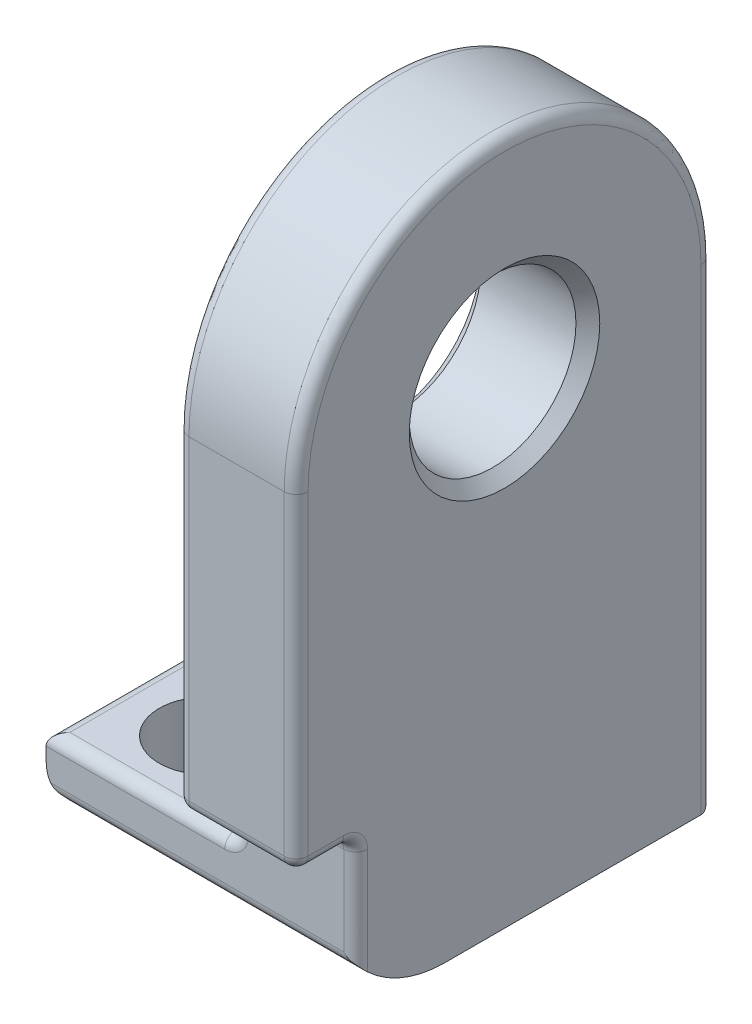
SolidWorks part; units mm, degrees
ref_plane "前视基准面" through (0, 0, 0) normal (0, 0, 1) x (1, 0, 0)
ref_plane "上视基准面" through (0, 0, 0) normal (0, 1, 0) x (1, 0, 0)
ref_plane "右视基准面" through (0, 0, 0) normal (1, 0, 0) x (0, 0, -1)
sketch "草图1" plane through (0, 0, 0) normal (1, 0, 0) x (0, 0, -1)
  line L0 (3.5, 0) -> (3.5, -8)
  line L1 (-3.5, 0) -> (-3.5, -8)
  line L2 (3.5, -8) -> (-3.5, -8)
  circle A0 centre (0, 0) radius 1.4
  arc A1 (3.5, 0) -> (-3.5, 0) centre (0, 0) ccw
  dimension "D1" = 3.5
  dimension "D2" = 8
extrude "凸台-拉伸1" add sketch "草图1" along normal blind 2
sketch "草图2" plane through (0, -8, 0) normal (0, -1, 0) x (1, 0, 0)
  line L0 (2, 3.5) -> (2, -3.5) construction
  line L1 (2, -3.5) -> (-3.2, -3.5)
  line L3 (2, 3.5) -> (-3.2, 3.5)
  line L4 (-3.2, -3.5) -> (-3.2, 3.5)
  line L6 (0, 3.5) -> (0, -3.5) construction
  line L7 (2, -3.5) -> (0, -3.5) construction
  line L8 (2, -3.5) -> (2, 3.5)
  line L9 (2, 3.5) -> (0, 3.5) construction
  circle A0 centre (-1.8, 1.2) radius 0.8
  circle A1 centre (-1.8, -2.3) radius 0.8
  dimension "D1" = 3.2
  dimension "D3" = 1.6
  dimension "D5" = 0
  dimension "D6" = 0
  dimension "D7" = 1.2
  dimension "D8" = 0
  dimension "D2" = 1.8
  dimension "D4" = 4.7
  dimension "D9" = 1.6
  dimension "D10" = 0
extrude "凸台-拉伸2" add sketch "草图2" against normal blind 1.5
sketch "草图5" plane through (0, -8, 0) normal (0, -1, 0) x (1, 0, 0)
  line L0 (2, 3.5) -> (-3.2, 3.5) construction
  line L1 (2, 3.5) -> (2, -3.5) construction
  line L3 (-4, 3.5) -> (2, 3.5)
  line L4 (-4, 3.5) -> (-4, 2.5)
  line L5 (-4, 2.5) -> (2, 2.5)
  line L6 (2, 3.5) -> (2, 2.5)
  dimension "D1" = 0
  dimension "D2" = 1
extrude "切除-拉伸1" cut sketch "草图5" against normal blind 2.5
sketch "草图6" plane through (-3.2, 0, 0) normal (-1, 0, 0) x (0, 0, 1)
  line L0 (0, 0) -> (0, -10.2943) construction
  line L2 (1, -8) -> (1, -8.3251)
  line L3 (1, -8.3251) -> (3.2771, -8.3251)
  line L4 (2.8974, -6) -> (3.2771, -6)
  line L5 (3.2771, -6) -> (3.2771, -8.3251)
  arc A0 (1, -8) -> (2.8974, -6) centre (1, -6.1) ccw
extrude "切除-拉伸2" cut sketch "草图6" against normal up to next
fillet "圆角1" radius 0.2 1 edges at (0, -6.5, -0.5)
fillet "圆角2" radius 0.2 21 edges at (-1.7, -6.5, -3.5) (-3.2, -6.5, -0.5) (2, 3.5, 0) (0, 3.5, 0) (2, -5.5, 3) (0, -5.5, 3) (2, -6.3831, 2.5) (0, -5.9, 2.5) (-0.0586, -6.4414, 2.5) (1, -5.5, 2.5) (-1.7, -6.5, 2.5) (2, -4, -3.5) (2, -2.75, 3.5) (-0.0586, -6.4414, -3.5) (0, -3.15, -3.5) (0, -2.75, 3.5) (-0.6, -8, -3.5) (1, -5.5, 3.5) (-3.2, -8, -1.25) (-3.2, -7.8067, 1.8349) (-0.6, -7.2662, 2.5)
chamfer "倒角1" distance 0.2 angle 45 2 edges at (0, 0, -1.4) (2, 0, -1.4)
